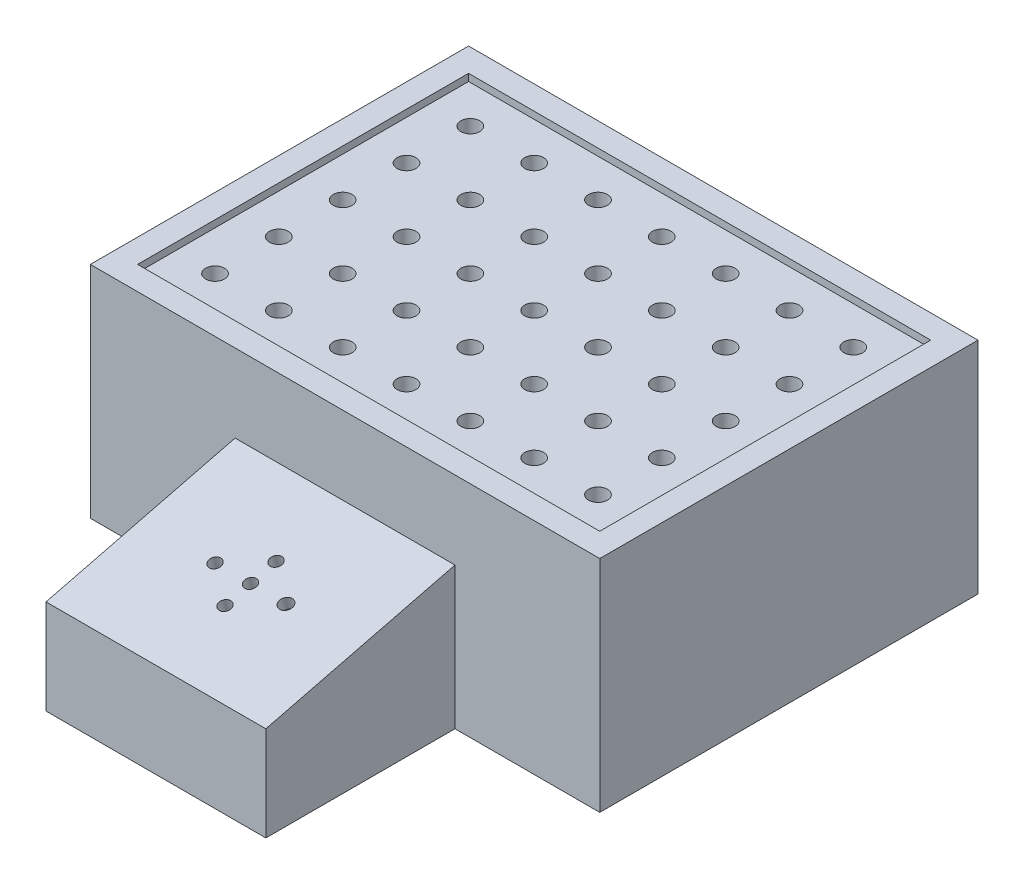
SolidWorks part; units mm, degrees
ref_plane "Front" through (0, 0, 0) normal (0, 0, 1) x (1, 0, 0)
ref_plane "Top" through (0, 0, 0) normal (0, 1, 0) x (1, 0, 0)
ref_plane "Right" through (0, 0, 0) normal (1, 0, 0) x (0, 0, -1)
sketch "Esboço1" plane through (0, 0, 0) normal (0, 1, 0) x (1, 0, 0)
  line L1 (107.75, -80) -> (-107.75, -80)
  line L2 (107.75, -80) -> (107.75, 80)
  line L3 (107.75, 80) -> (-107.75, 80)
  line L4 (-107.75, -80) -> (-107.75, 80)
  line L5 (107.75, -80) -> (-107.75, 80) construction
  line L6 (107.75, 80) -> (-107.75, -80) construction
  point P0 (0, 0)
  dimension "D1" = 215.5
  dimension "D2" = 160
extrude "Ressalto-extrusão1" add sketch "Esboço1" along normal blind 90
sketch "Esboço2" plane through (0, 0, 80) normal (0, 0, 1) x (1, 0, 0)
  line L0 (46.5, 0) -> (-46.5, 0)
  line L1 (-107.75, 0) -> (107.75, 0) construction
  line L2 (-46.5, 0) -> (-46.5, 60)
  line L3 (-46.5, 60) -> (46.5, 60)
  line L4 (46.5, 60) -> (46.5, 0)
  point P6 (0, 0)
  dimension "D1" = 93
  dimension "D2" = 60
extrude "Ressalto-extrusão2" add sketch "Esboço2" along normal blind 80
sketch "Esboço3" plane through (-46.5, 0, 0) normal (-1, 0, 0) x (0, 0, 1)
  line L0 (160, 60) -> (160, 40)
  line L1 (160, 0) -> (160, 60) construction
  line L2 (160, 40) -> (80, 60)
  line L3 (80, 60) -> (160, 60)
  dimension "D1" = 20
extrude "Corte-extrusão1" cut sketch "Esboço3" against normal up to next
sketch "Esboço4" plane through (0, 75.2941, 18.8235) normal (0, 0.9701, 0.2425) x (1, 0, 0)
  line L0 (-46.5, -63.0593) -> (-46.5, -145.5214) construction
  line L1 (-46.5, -104.2903) -> (46.5, -104.2903) construction
  line L2 (46.5, -145.5214) -> (46.5, -63.0593) construction
  line L3 (0, -63.0593) -> (0, -145.5214) construction
  line L4 (46.5, -63.0593) -> (-46.5, -63.0593) construction
  line L5 (46.5, -145.5214) -> (-46.5, -145.5214) construction
  line L6 (15, -104.2903) -> (-15, -104.2903)
  line L7 (0, -115.4097) -> (0, -93.1709)
  circle A0 centre (0, -93.1709) radius 2.5
  circle A1 centre (15, -104.2903) radius 2.7281
  circle A2 centre (-15, -104.2903) radius 2.5
  circle A3 centre (0, -115.4097) radius 2.5
  circle A4 centre (0, -104.2903) radius 2.5
  point P15 (0, -104.2903)
  point P18 (0, -104.2903)
extrude "Corte-extrusão2" cut sketch "Esboço4" against normal blind 5
sketch "Esboço5" plane through (0, 90, 0) normal (0, 1, 0) x (1, 0, 0)
  line L1 (97.75, -70) -> (-97.75, -70)
  line L2 (97.75, -70) -> (97.75, 70)
  line L3 (97.75, 70) -> (-97.75, 70)
  line L4 (-97.75, -70) -> (-97.75, 70)
  line L5 (97.75, -70) -> (-97.75, 70) construction
  line L6 (97.75, 70) -> (-97.75, -70) construction
  line L7 (-107.75, 80) -> (107.75, 80)
  line L8 (-107.75, 80) -> (-107.75, -80)
  line L9 (-107.75, -80) -> (107.75, -80)
  line L10 (107.75, 80) -> (107.75, -80)
  point P0 (0, 0)
  dimension "D1" = 10
  dimension "D2" = 10
  dimension "D3" = 10
  dimension "D4" = 10
extrude "Ressalto-extrusão3" add sketch "Esboço5" along normal blind 3
sketch "Esboço6" plane through (0, 90, 0) normal (0, 1, 0) x (1, 0, 0)
  line L0 (97.75, 70) -> (-97.75, 70) construction
  line L3 (-81, 67) -> (-94.75, 67)
  line L4 (-94.75, 54) -> (-94.75, 67)
  line L5 (94.75, -67) -> (-94.75, 67) construction
  line L6 (94.75, 67) -> (-94.75, -67) construction
  line L7 (-97.75, 70) -> (-97.75, -70) construction
  line L8 (-94.75, 67) -> (-94.75, 54) construction
  line L9 (-94.75, 67) -> (-81, 67) construction
  circle A0 centre (-81, 54) radius 4
  circle A1 centre (-54, 54) radius 4
  circle A2 centre (-27, 54) radius 4
  circle A3 centre (0, 54) radius 4
  circle A4 centre (27, 54) radius 4
  circle A5 centre (54, 54) radius 4
  circle A6 centre (81, 54) radius 4
  circle A7 centre (-54, 27) radius 4
  circle A8 centre (-27, 27) radius 4
  circle A9 centre (0, 27) radius 4
  circle A10 centre (27, 27) radius 4
  circle A11 centre (54, 27) radius 4
  circle A12 centre (81, 27) radius 4
  circle A13 centre (-54, 0) radius 4
  circle A14 centre (-27, 0) radius 4
  circle A15 centre (0, 0) radius 4
  circle A16 centre (27, 0) radius 4
  circle A17 centre (54, 0) radius 4
  circle A18 centre (81, 0) radius 4
  circle A19 centre (-54, -27) radius 4
  circle A20 centre (-27, -27) radius 4
  circle A21 centre (0, -27) radius 4
  circle A22 centre (27, -27) radius 4
  circle A23 centre (54, -27) radius 4
  circle A24 centre (81, -27) radius 4
  circle A25 centre (-54, -54) radius 4
  circle A26 centre (-27, -54) radius 4
  circle A27 centre (0, -54) radius 4
  circle A28 centre (27, -54) radius 4
  circle A29 centre (54, -54) radius 4
  circle A30 centre (81, -54) radius 4
  circle A31 centre (-81, 27) radius 4
  circle A32 centre (-81, 0) radius 4
  circle A33 centre (-81, -27) radius 4
  circle A34 centre (-81, -54) radius 4
  point P0 (0, 0)
  dimension "D5" = 7
  dimension "D1" = 3
  dimension "D2" = 3
  dimension "D3" = 13
  dimension "D4" = 13.75
  dimension "D6" = 5
extrude "Corte-extrusão3" cut sketch "Esboço6" against normal blind 10 contours A0 | A1 | A2 | A3 | A4 | A5 | A6 | A12 | A11 | A10 | A9 | A8 | A7 | A31 | A32 | A13 | A14 | A15 | A16 | A17 | A18 | A24 | A23 | A22 | A21 | A20 | A19 | A33 | A34 | A25 | A26 | A27 | A28 | A29 | A30
